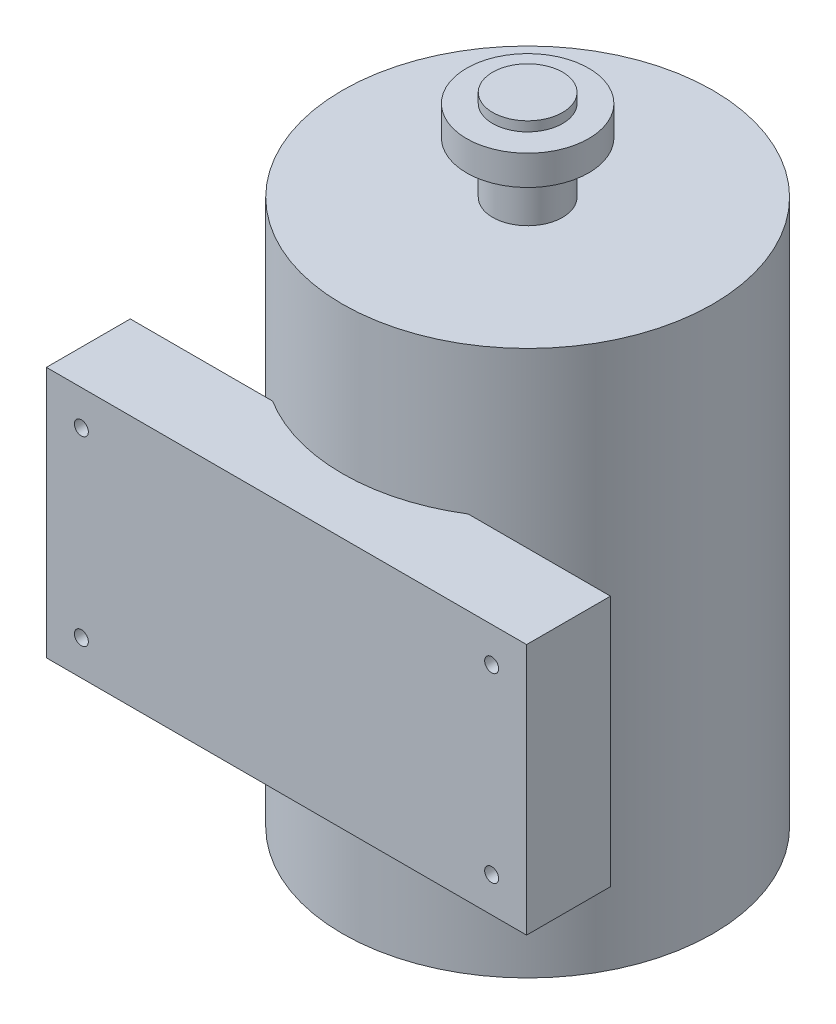
SolidWorks part; units mm, degrees
ref_plane "Front Plane" through (0, 0, 0) normal (0, 0, 1) x (1, 0, 0)
ref_plane "Top Plane" through (0, 0, 0) normal (0, 1, 0) x (1, 0, 0)
ref_plane "Right Plane" through (0, 0, 0) normal (1, 0, 0) x (0, 0, -1)
sketch "Sketch1" plane through (0, 0, 0) normal (0, 1, 0) x (1, 0, 0)
  circle A0 centre (0, 0) radius 53
  dimension "D1" = 106
extrude "Boss-Extrude1" add sketch "Sketch1" along normal mid plane 156
sketch "Sketch2" plane through (0, 78, 0) normal (0, 1, 0) x (1, 0, 0)
  circle A0 centre (0, 0) radius 10
  dimension "D1" = 20
extrude "Boss-Extrude2" add sketch "Sketch2" along normal blind 26
ref_plane "Plane1" through (0, 0, 69) normal (0, 0, -1) x (-1, 0, 0)
ref_plane "Plane2" through (0, 97, 0) normal (0, 1, 0) x (1, 0, 0)
sketch "Sketch9" plane through (0, 97, 0) normal (0, 1, 0) x (1, 0, 0)
  circle A0 centre (0, 0) radius 17.4625
  dimension "D1" = 34.925
extrude "Boss-Extrude4" add sketch "Sketch9" along normal mid plane 8.5
sketch "Sketch12" plane through (0, 0, 69) normal (0, 0, -1) x (-1, 0, 0)
  line L1 (68.7, 36) -> (-68.7, 36)
  line L2 (68.7, 36) -> (68.7, -36)
  line L3 (68.7, -36) -> (-68.7, -36)
  line L4 (-68.7, 36) -> (-68.7, -36)
  line L5 (68.7, 36) -> (-68.7, -36) construction
  line L6 (68.7, -36) -> (-68.7, 36) construction
  point P0 (0, 0)
  dimension "D1" = 137.4
  dimension "D2" = 72
extrude "Boss-Extrude6" add sketch "Sketch12" along normal blind 24
sketch "Sketch13" plane through (0, 0, 69) normal (0, 0, 1) x (1, 0, 0)
  line L0 (68.7, 36) -> (68.7, -36) construction
  line L1 (-68.7, -36) -> (-68.7, 36) construction
  line L2 (-68.7, 36) -> (68.7, 36) construction
  line L3 (68.7, -36) -> (-68.7, -36) construction
  circle A0 centre (-58.7, -26) radius 2
  circle A1 centre (-58.7, 26) radius 2
  circle A2 centre (58.7, 26) radius 2
  circle A3 centre (58.7, -26) radius 2
  dimension "D1" = 4
  dimension "D2" = 4
  dimension "D3" = 4
  dimension "D4" = 4
  dimension "D5" = 10
  dimension "D6" = 10
  dimension "D7" = 10
  dimension "D8" = 10
  dimension "D9" = 10
  dimension "D10" = 10
  dimension "D11" = 10
  dimension "D12" = 10
extrude "Cut-Extrude2" cut sketch "Sketch13" against normal blind 24
